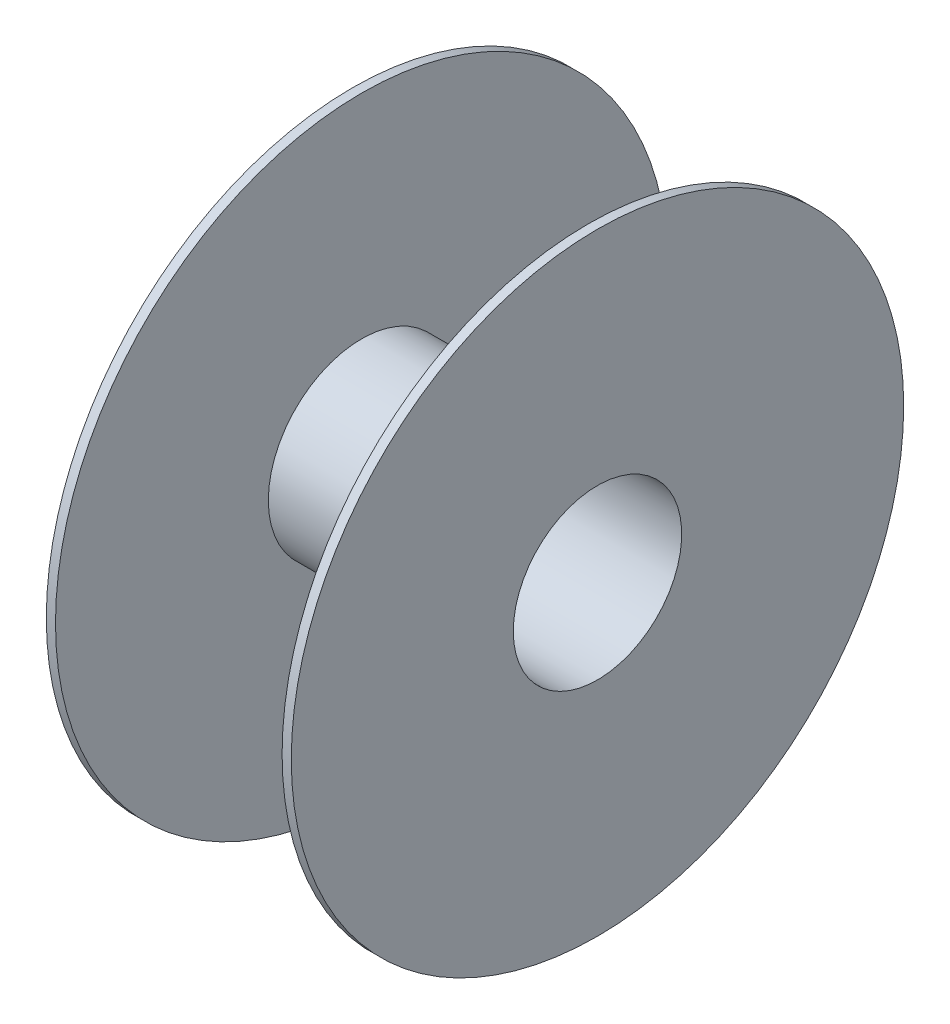
SolidWorks part; units mm, degrees
ref_plane "Front" through (0, 0, 0) normal (0, 0, 1) x (1, 0, 0)
ref_plane "Top" through (0, 0, 0) normal (0, 1, 0) x (1, 0, 0)
ref_plane "Right" through (0, 0, 0) normal (1, 0, 0) x (0, 0, -1)
sketch "Sketch1" plane through (0, 0, 0) normal (0, 0, 1) x (1, 0, 0)
  line L0 (-40, 0) -> (0, 0) construction
  line L1 (0, 0) -> (0, 30.5) construction
  line L2 (37, 30.5) -> (-37, 30.5)
  line L3 (-37, 30.5) -> (-37, 100)
  line L4 (-37, 100) -> (-40, 100)
  line L5 (-40, 100) -> (-40, 27.5)
  line L6 (-40, 27.5) -> (40, 27.5)
  line L7 (40, 100) -> (40, 27.5)
  line L8 (37, 100) -> (40, 100)
  line L9 (37, 30.5) -> (37, 100)
  point P13 (0, 27.5)
  dimension "D1" = 80
  dimension "D2" = 200
  dimension "D3" = 55
  dimension "D4" = 3
  dimension "D5" = 3
revolve "Revolve1" add sketch "Sketch1" angle 360 about L0
